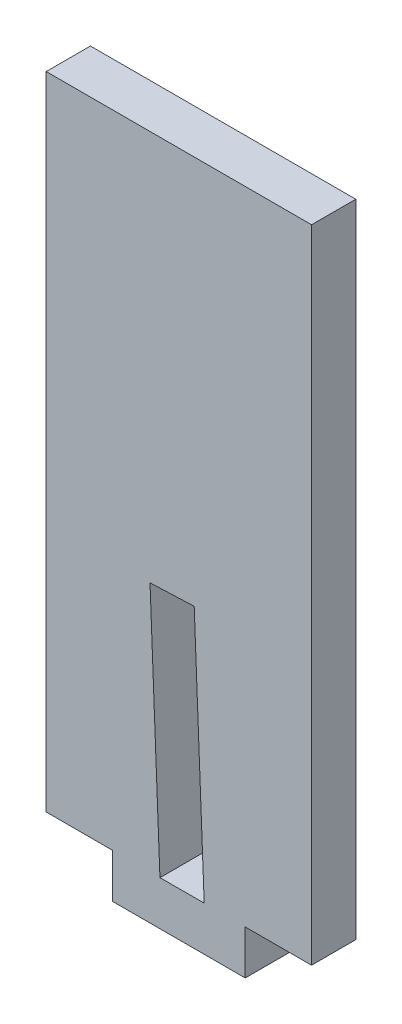
SolidWorks part; units mm, degrees
ref_plane "前视基准面" through (0, 0, 0) normal (0, 0, 1) x (1, 0, 0)
ref_plane "上视基准面" through (0, 0, 0) normal (0, 1, 0) x (1, 0, 0)
ref_plane "右视基准面" through (0, 0, 0) normal (1, 0, 0) x (0, 0, -1)
sketch "草图1" plane through (0, 0, 0) normal (0, 0, 1) x (1, 0, 0)
  line L0 (-6, 0) -> (-6, 15)
  line L1 (-6, 0) -> (-3, 0)
  line L3 (6, 0) -> (6, 15)
  line L4 (-3, 0) -> (-3, -2)
  line L6 (-3, -2) -> (3, -2)
  line L7 (3, 0) -> (3, -2)
  line L8 (-6, 15) -> (-6, 30.0788)
  line L9 (-6, 30.0788) -> (6, 30.0788)
  line L10 (6, 30.0788) -> (6, 15)
  line L11 (3, 0) -> (6, 0)
extrude "凸台-拉伸1" add sketch "草图1" along normal blind 2 contours L9 L10 L3 L11 L7 L6 L4 L1 L0 L8
sketch "草图3" plane through (0, 0, 2) normal (0, 0, 1) x (1, 0, 0)
  line L0 (17.7523, 29) -> (-31.8073, 29) construction
  line L1 (17.7523, 29) -> (-31.8073, 29)
  line L2 (10.2989, 29) -> (10.2989, 34.1435)
  line L3 (10.2989, 34.1435) -> (-9.585, 34.1435)
  line L4 (-9.585, 34.1435) -> (-9.585, 29)
  line M2 (-6, 30.0788) -> (-6, 0)
  line M8 (6, 0) -> (6, 30.0788)
  line M9 (6, 30.0788) -> (-6, 30.0788)
extrude "切除-拉伸2" cut sketch "草图3" against normal blind 10 contours L1 M8 M9 M2 | L3 L4 L1 L2 M2 M9 M8
sketch "草图4" plane through (0, 0, 2) normal (0, 0, 1) x (1, 0, 0)
  line L0 (-1.2915, 10.9651) -> (0.6927, 11.4028)
  line L1 (-0.8571, 0) -> (-1.2915, 10.9651)
  line L2 (1.1443, 0.0058) -> (0.6927, 11.4028)
  line L3 (1.1443, 0.0058) -> (-0.8571, 0)
  line L4 (1.1443, 0.0058) -> (-0.8571, 0)
  line L5 (1.1443, 0.0058) -> (0.6927, 11.4028)
  line L6 (-0.8571, 0) -> (-1.2915, 10.9651)
  line L8 (0.6927, 11.4028) -> (-1.3058, 11.3236)
  line L9 (-1.2915, 10.9651) -> (-1.3058, 11.3236)
extrude "切除-拉伸3" cut sketch "草图4" against normal blind 2
